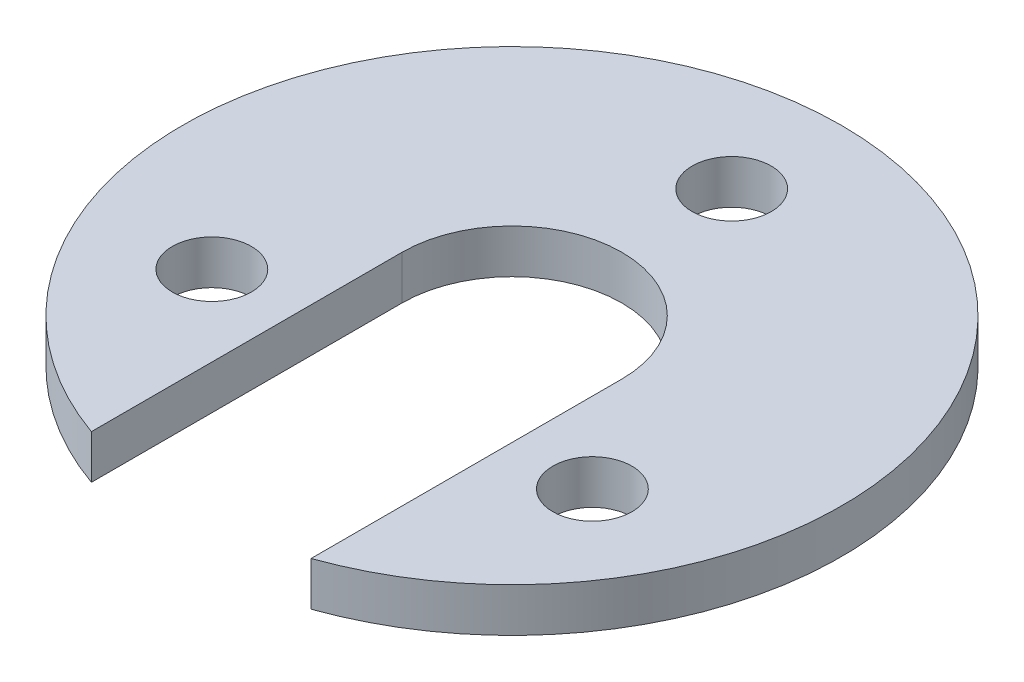
SolidWorks part; units mm, degrees
ref_plane "Front Plane" through (0, 0, 0) normal (0, 0, 1) x (1, 0, 0)
ref_plane "Top Plane" through (0, 0, 0) normal (0, 1, 0) x (1, 0, 0)
ref_plane "Right Plane" through (0, 0, 0) normal (1, 0, 0) x (0, 0, -1)
sketch "Sketch1" plane through (0, 0, 0) normal (0, 1, 0) x (1, 0, 0)
  line L0 (0, 0) -> (0, -75) construction
  line L1 (25, 0) -> (25, -70.7107)
  line L2 (-25, 0) -> (-25, -70.7107)
  arc A0 (25, -70.7107) -> (-25, -70.7107) centre (0, 0) ccw
  circle A1 centre (0, 50) radius 9
  circle A2 centre (43.3013, -25) radius 9
  circle A3 centre (-43.3013, -25) radius 9
  arc A4 (25, 0) -> (-25, 0) centre (0, 0) ccw
  point P3 (0, -37.5)
  point P12 (0, 0)
  dimension "D1" = 150
  dimension "D2" = 3
  dimension "D3" = 50
  dimension "D4" = 50
extrude "Boss-Extrude1" add sketch "Sketch1" along normal blind 10
